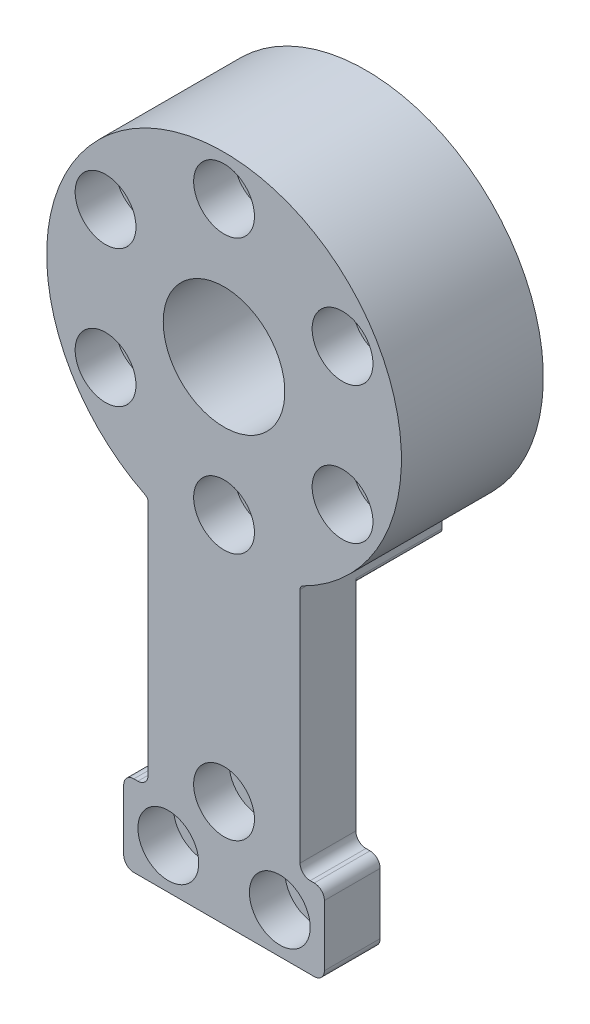
SolidWorks part; units mm, degrees
ref_plane "前视基准面" through (0, 0, 0) normal (0, 0, 1) x (1, 0, 0)
ref_plane "上视基准面" through (0, 0, 0) normal (0, 1, 0) x (1, 0, 0)
ref_plane "右视基准面" through (0, 0, 0) normal (1, 0, 0) x (0, 0, -1)
ref_plane "基准面1" through (0, 0, 14) normal (0, 0, 1) x (1, 0, 0)
sketch "草图1" plane through (0, 0, 14) normal (0, 0, 1) x (1, 0, 0)
  line L0 (-7.5, -15.8114) -> (-7.5, -48.5)
  line L1 (-7.5, -48.5) -> (7.5, -48.5)
  line L2 (7.5, -48.5) -> (7.5, -15.8114)
  arc A0 (7.5, -15.8114) -> (-7.5, -15.8114) centre (0, 0) ccw
extrude "凸台-拉伸1" add sketch "草图1" against normal blind 14
sketch "草图2" plane through (0, 0, 0) normal (0, 0, -1) x (-1, 0, 0)
  line L0 (7.5, -48.5) -> (7.5, -18.2705)
  line L1 (-7.5, -18.2705) -> (-7.5, -48.5)
  line L2 (-7.5, -48.5) -> (7.5, -48.5)
  arc A0 (7.5, -18.2705) -> (-7.5, -18.2705) centre (0, 0) cw
extrude "切除-拉伸1" cut sketch "草图2" against normal blind 8.5
sketch "草图3" plane through (-7.5, 0, 0) normal (-1, 0, 0) x (0, 0, 1)
  line L0 (14, -40.501) -> (14, -48.5)
  line L1 (14, -48.5) -> (8.5, -48.5)
  line L2 (8.5, -48.5) -> (8.5, -40.501)
  line L3 (8.5, -40.501) -> (14, -40.501)
extrude "凸台-拉伸2" add sketch "草图3" along normal blind 2.4
sketch "草图4" plane through (7.5, 0, 0) normal (1, 0, 0) x (0, 0, -1)
  line L0 (-8.5, -40.501) -> (-8.5, -48.5)
  line L1 (-8.5, -48.5) -> (-14, -48.5)
  line L2 (-14, -48.5) -> (-14, -40.501)
  line L3 (-14, -40.501) -> (-8.5, -40.501)
extrude "凸台-拉伸3" add sketch "草图4" along normal blind 2.4
hole_wizard "Ø12.0 (12) 直径孔1" positions "草图6" profile "草图5" hole size "Ø12.0" standard "ANSI Metric"
sketch "草图6" plane through (0, 0, 0) normal (0, 0, -1) x (-1, 0, 0)
  point P0 (0, 0)
sketch "草图5" plane through (0, 0, 0) normal (1, 0, 0) x (0, 1, 0)
  line L0 (0, 0) -> (0, 14)
  line L1 (0, 14) -> (6, 14)
  line L2 (6, 14) -> (6, 0)
  line L5 (6, 0) -> (0, 0)
  line L11 (0, -6.35) -> (0, 107.95) construction
  dimension "通孔孔直径" = 12
  dimension "通孔孔深度" = 14
hole_wizard "M3 六角头机械螺钉的柱形沉头孔1" positions "草图8" profile "草图7" counterbore size "M3" standard "ANSI Metric"
sketch "草图8" plane through (0, 0, 14) normal (0, 0, 1) x (1, 0, 0)
  point P0 (0, 13.5)
  point P1 (11.6913, 6.75)
  point P2 (11.6913, -6.75)
  point P3 (0, -13.5)
  point P4 (-11.6913, -6.75)
  point P5 (-11.6913, 6.75)
sketch "草图7" plane through (0, 13.5, 14) normal (1, 0, 0) x (0, -1, 0)
  line L0 (0, 0) -> (0, 14)
  line L1 (0, 14) -> (1.6, 14)
  line L3 (1.6, 14) -> (1.6, 4)
  line L4 (1.6, 4) -> (3, 4)
  line L5 (3, 4) -> (3, 0)
  line L7 (3, 0) -> (0, 0)
  line L11 (0, -6.35) -> (0, 107.95) construction
  dimension "通孔孔直径" = 3.2
  dimension "通孔孔深度" = 14
  dimension "柱形沉头孔直径" = 6
  dimension "柱形沉头孔深度" = 4
hole_wizard "M3 六角头机械螺钉的柱形沉头孔2" positions "草图10" profile "草图9" counterbore size "M3" standard "ANSI Metric"
sketch "草图10" plane through (0, 0, 14) normal (0, 0, 1) x (1, 0, 0)
  point P0 (0, -38)
  point P1 (5.501, -44.5005)
  point P2 (-5.499, -44.5005)
sketch "草图9" plane through (0, -38, 14) normal (1, 0, 0) x (0, -1, 0)
  line L0 (0, 0) -> (0, 14)
  line L1 (0, 14) -> (1.6, 14)
  line L3 (1.6, 14) -> (1.6, 3.5)
  line L4 (1.6, 3.5) -> (3, 3.5)
  line L5 (3, 3.5) -> (3, 0)
  line L7 (3, 0) -> (0, 0)
  line L11 (0, -6.35) -> (0, 107.95) construction
  dimension "通孔孔直径" = 3.2
  dimension "通孔孔深度" = 14
  dimension "柱形沉头孔直径" = 6
  dimension "柱形沉头孔深度" = 3.5
fillet "圆角1" radius 0.5 4 edges at (7.5, -15.8114, 7) (-7.5, -15.8114, 7) (7.5, -18.2705, 4.25) (-7.5, -18.2705, 4.25)
fillet "圆角2" radius 1 6 edges at (-9.9, -40.501, 11.25) (7.5, -40.501, 11.25) (-7.5, -40.501, 11.25) (-9.9, -48.5, 11.25) (9.9, -48.5, 11.25) (9.9, -40.501, 11.25)
